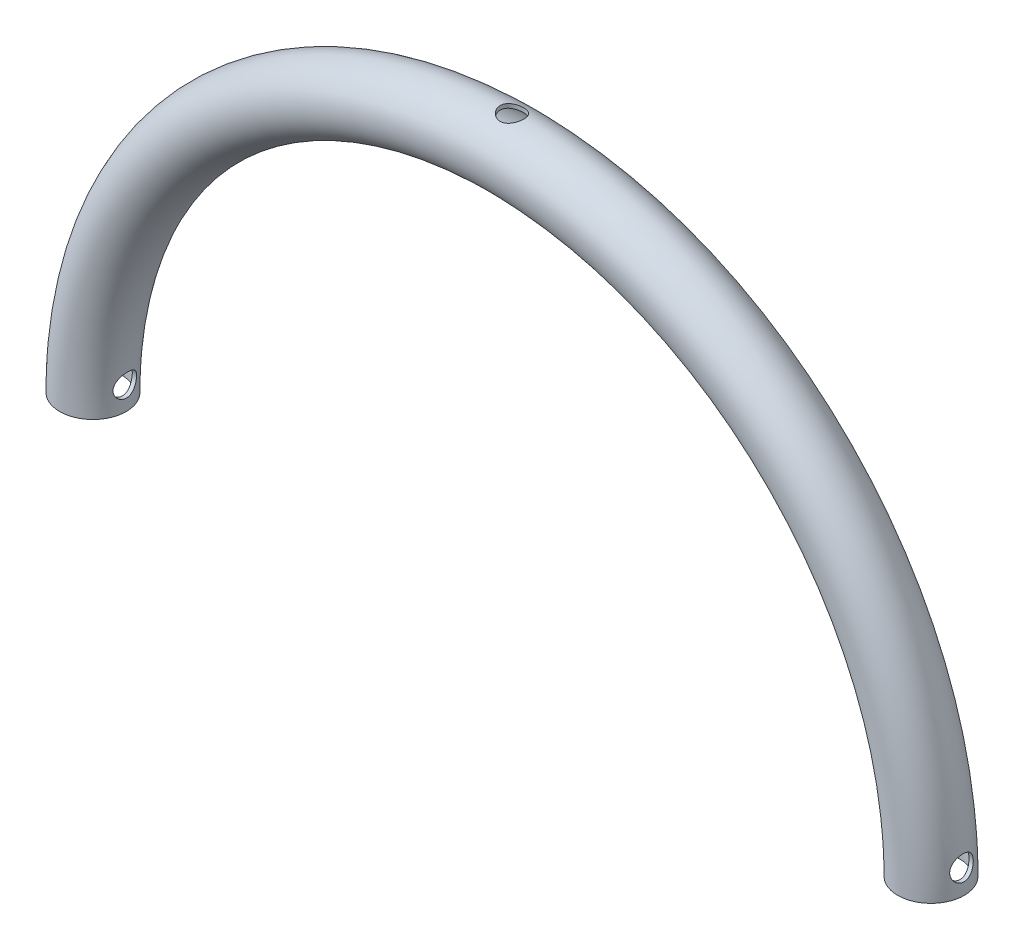
SolidWorks part; units mm, degrees
material "Galvanized Steel"
ref_plane "Front Plane" through (0, 0, 0) normal (0, 0, 1) x (1, 0, 0)
ref_plane "Top Plane" through (0, 0, 0) normal (0, 1, 0) x (1, 0, 0)
ref_plane "Right Plane" through (0, 0, 0) normal (1, 0, 0) x (0, 0, -1)
sketch "Sketch1" plane through (0, 0, 0) normal (0, 1, 0) x (1, 0, 0)
  circle A0 centre (0, 0) radius 7.8994
  circle A1 centre (0, 0) radius 8.9662
sketch "Sketch2" plane through (0, 0, 0) normal (0, 0, 1) x (1, 0, 0)
  arc A0 (0, 0) -> (226.06, 0) centre (113.03, 0) cw
sweep "Sweep1" add profiles "Sketch1" path "Sketch2"
sketch "Sketch3" plane through (0, 0, 0) normal (1, 0, 0) x (0, 0, -1)
  line L0 (-8.9662, 0) -> (8.9662, 0) construction
  circle A0 centre (0, 6.35) radius 3.175
  dimension "D1" = 6.35
extrude "Cut-Extrude1" cut sketch "Sketch3" against normal through all and the other way through all
sketch "Sketch5" plane through (0, 0, 0) normal (0, 0, 1) x (1, 0, 0)
  line L0 (113.03, 0) -> (113.03, 155.7767) construction
  circle A0 centre (113.03, 0) radius 121.9962 construction
sketch "Sketch6" plane through (0, 0, 0) normal (0, 1, 0) x (1, 0, 0)
  circle A0 centre (113.03, 0) radius 3.175
extrude "Cut-Extrude4" cut sketch "Sketch6" against normal blind 2.54 and the other way through all
sketch "Sketch8" plane through (0, 0, 0) normal (0, 0, 1) x (1, 0, 0)
  line L0 (235.0262, 0) -> (-8.9662, 0) construction
  line L1 (-8.9662, 0) -> (113.03, 0) construction
  line L2 (113.03, 0) -> (113.03, 134.5237) construction
  line L3 (109.855, 121.9549) -> (116.205, 121.9549) construction
  line L4 (-11.87, 6.35) -> (241.4728, 6.35) construction
  point P12 (113.03, 6.35)
  dimension "D1" = 6.35
ref_plane "Plane1" through (113.03, 0, 0) normal (1, 0, 0) x (0, 0, -1)
sketch "Sketch9" plane through (113.03, 0, 0) normal (1, 0, 0) x (0, 0, -1)
  line L0 (0, 6.35) -> (-6.35, 6.35) construction
  line L1 (0, 0) -> (-6.35, 0) construction
